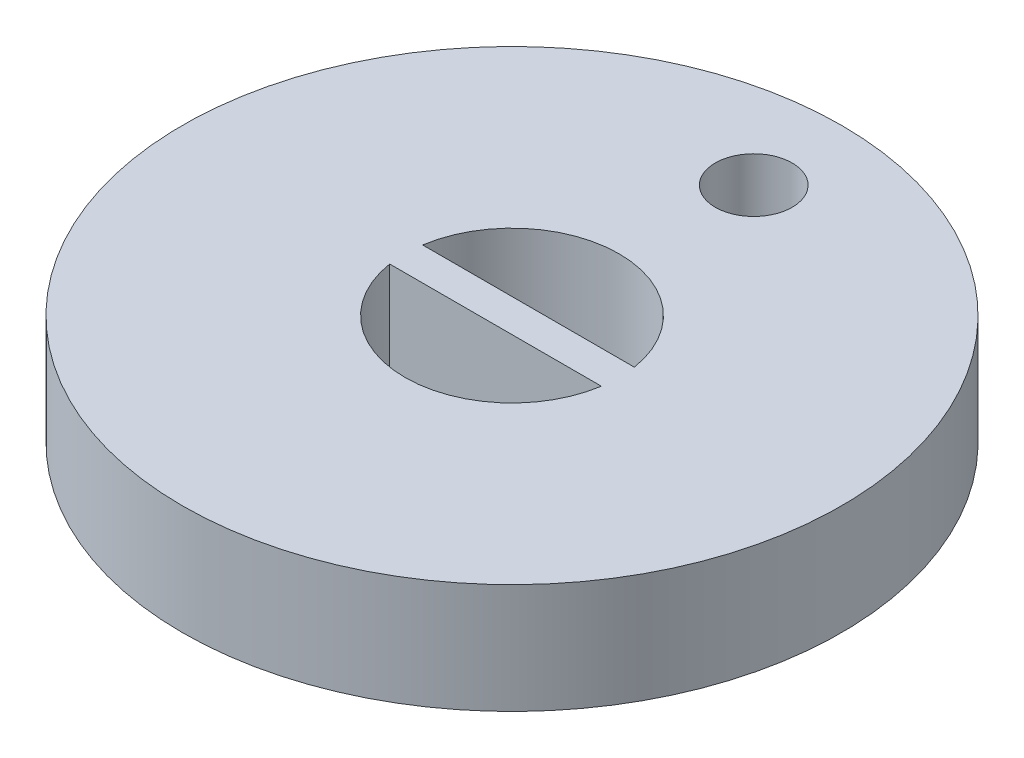
SolidWorks part; units mm, degrees
ref_plane "Front Plane" through (0, 0, 0) normal (0, 0, 1) x (1, 0, 0)
ref_plane "Top Plane" through (0, 0, 0) normal (0, 1, 0) x (1, 0, 0)
ref_plane "Right Plane" through (0, 0, 0) normal (1, 0, 0) x (0, 0, -1)
sketch "Sketch1" plane through (0, 0, 0) normal (0, 1, 0) x (1, 0, 0)
  circle A0 centre (0, 0) radius 6
extrude "Boss-Extrude1" add sketch "Sketch1" along normal blind 2
sketch "Sketch2" plane through (0, 2, 0) normal (0, 1, 0) x (1, 0, 0)
  line L0 (0, 0) -> (0, -0.3)
  line L1 (0, 0) -> (0, 0.3)
  line L2 (0, 0.3) -> (-2.5946, 0.3)
  line L4 (-2.5946, 0.3) -> (2.9563, 0.3)
  line L5 (-2.5946, 0.3) -> (-2.5946, -0.3)
  line L6 (-2.5946, -0.3) -> (2.9563, -0.3)
  line L7 (2.9563, 0.3) -> (2.9563, -0.3)
  circle A0 centre (0, 0) radius 1.95
extrude "Cut-Extrude1" cut sketch "Sketch2" against normal blind 4 contours L4 A0 L2 | L6 A0
sketch "Sketch3" plane through (0, 2, 0) normal (0, 1, 0) x (1, 0, 0)
  circle A0 centre (0.1436, 4.2574) radius 0.7
extrude "Cut-Extrude2" cut sketch "Sketch3" against normal blind 4
